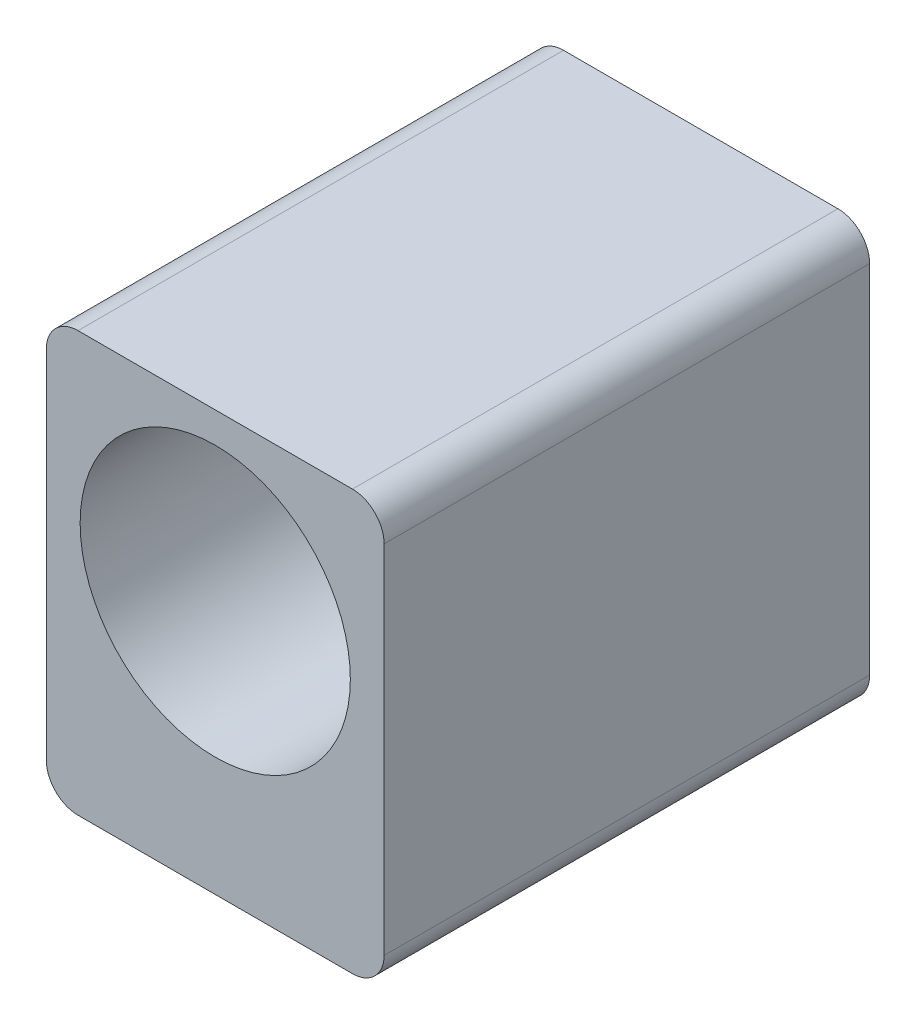
SolidWorks part; units mm, degrees
ref_plane "Front Plane" through (0, 0, 0) normal (0, 0, 1) x (1, 0, 0)
ref_plane "Top Plane" through (0, 0, 0) normal (0, 1, 0) x (1, 0, 0)
ref_plane "Right Plane" through (0, 0, 0) normal (1, 0, 0) x (0, 0, -1)
sketch "Sketch1" plane through (0, 0, 0) normal (0, 0, 1) x (1, 0, 0)
  line L0 (-13, -24.064) -> (13, -24.064)
  line L1 (16, -21.064) -> (16, 12.7)
  line L2 (13, 15.7) -> (-13, 15.7)
  line L3 (-16, 12.7) -> (-16, -21.064)
  arc A0 (13, -24.064) -> (16, -21.064) centre (13, -21.064) ccw
  arc A1 (16, 12.7) -> (13, 15.7) centre (13, 12.7) ccw
  arc A2 (-13, 15.7) -> (-16, 12.7) centre (-13, 12.7) ccw
  arc A3 (-16, -21.064) -> (-13, -24.064) centre (-13, -21.064) ccw
  circle A4 centre (0, 0) radius 12.8
extrude "Boss-Extrude1" add sketch "Sketch1" along normal mid plane 46
ref_plane "Plane1" through (0, -24.064, 0) normal (0, 1, 0) x (1, 0, 0)
sketch "Sketch2" plane through (0, -24.064, 0) normal (0, 1, 0) x (1, 0, 0)
  circle A0 centre (12, -17.5) radius 2
  circle A1 centre (-12, 17.5) radius 2
extrude "Cut-Extrude1" cut sketch "Sketch2" along normal blind 9
